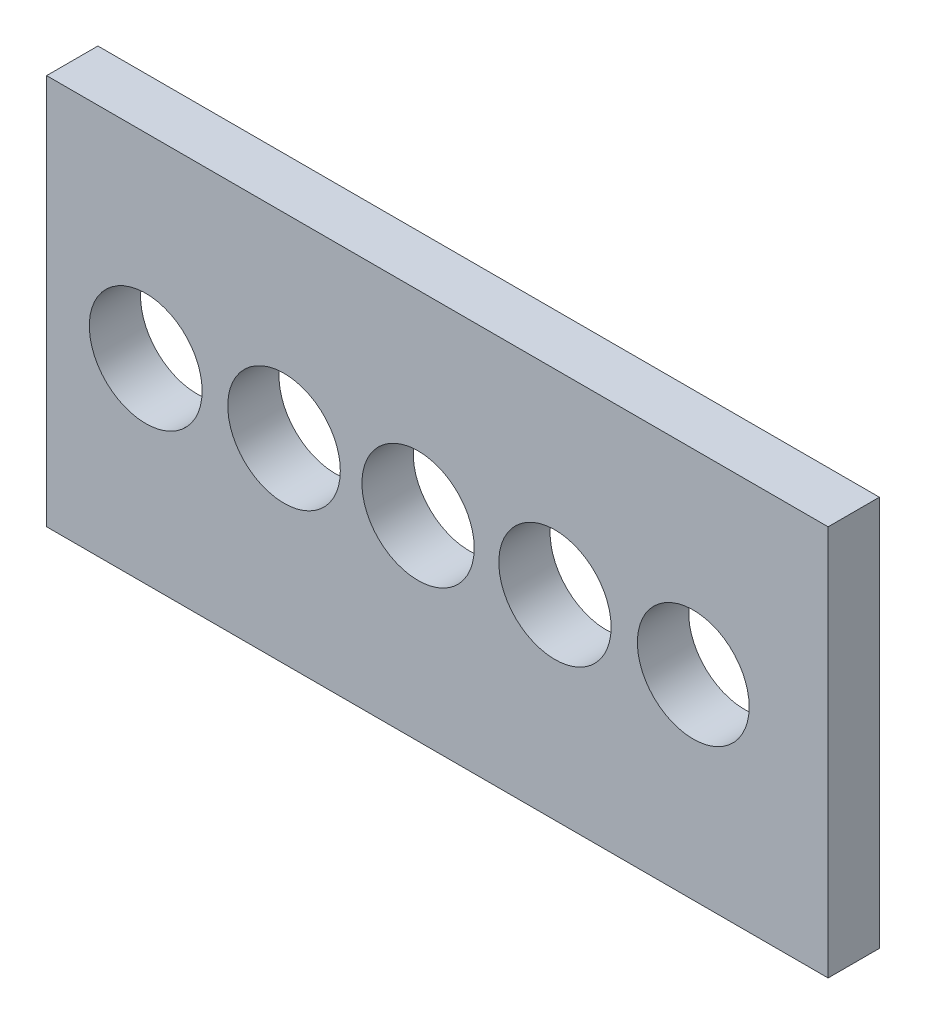
SolidWorks part; units mm, degrees
ref_plane "Front Plane" through (0, 0, 0) normal (0, 0, 1) x (1, 0, 0)
ref_plane "Top Plane" through (0, 0, 0) normal (0, 1, 0) x (1, 0, 0)
ref_plane "Right Plane" through (0, 0, 0) normal (1, 0, 0) x (0, 0, -1)
sketch "Sketch1" plane through (0, 0, 0) normal (0, 0, 1) x (1, 0, 0)
  line L1 (0, 0) -> (152.4, 0)
  line L2 (0, 0) -> (0, -76.2)
  line L3 (0, -76.2) -> (152.4, -76.2)
  line L4 (152.4, 0) -> (152.4, -76.2)
  circle A0 centre (19.3263, -38.1) radius 11
  circle A2 centre (46.2997, -38.1) radius 10.975
  circle A3 centre (72.4389, -38.1) radius 10.95
  circle A4 centre (99.1342, -38.1) radius 10.95
  circle A5 centre (126.1077, -38.1) radius 10.9
  dimension "D1" = 22
extrude "Boss-Extrude1" add sketch "Sketch1" along normal blind 10
